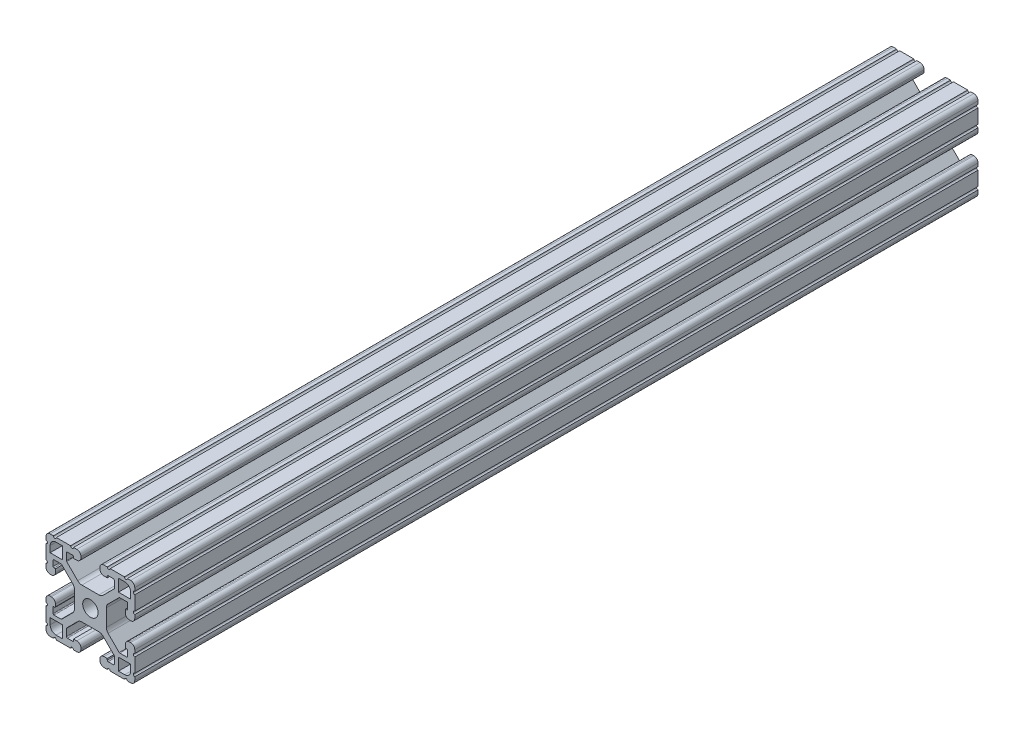
SolidWorks part; units mm, degrees
ref_plane "Front Plane" through (0, 0, 0) normal (0, 0, 1) x (1, 0, 0)
ref_plane "Top Plane" through (0, 0, 0) normal (0, 1, 0) x (1, 0, 0)
ref_plane "Right Plane" through (0, 0, 0) normal (1, 0, 0) x (0, 0, -1)
sketch "Sketch1" plane through (0, 0, 0) normal (0, 0, 1) x (1, 0, 0)
  line L0 (0, -19.05) -> (0, 19.05) construction
  line L1 (19.05, 0) -> (-19.05, 0) construction
  line L2 (4.064, 19.05) -> (-4.064, 19.05) construction
  line L3 (0, -6.858) -> (0, 6.858) construction
  line L4 (-4.064, 19.05) -> (-4.064, 14.986) construction
  line L5 (19.05, -10.287) -> (19.05, 10.287) construction
  line L6 (0, -3.302) -> (0, 3.302) construction
  point P4 (0, 0)
  point P8 (0, 0)
  point P11 (0, 19.05)
  point P14 (0, 0)
  point P18 (19.05, 0)
  point P21 (0, 0)
  dimension "Rail Width" = 38.1
  dimension "Rail Height" = 38.1
  dimension "T-Slot Width" = 8.128
  dimension "Thickness" = 4.064
  dimension "Opening Width" = 20.574
  dimension "Center Hole Diameter" = 6.604
  dimension "Slot Depth" = 12.192
sketch "Sketch2" plane through (0, 0, 0) normal (1, 0, 0) x (0, 0, -1)
  line L0 (-180.975, 0) -> (180.975, 0) construction
  line L1 (0, 19.05) -> (0, -19.05) construction
  line L2 (-25.4, 19.05) -> (25.4, 19.05) construction
  line L4 (3048, -19.05) -> (-3048, -19.05) construction
  point P0 (130.175, 0)
  point P3 (-130.175, 0)
  point P4 (0, 0)
  dimension "D1" = 50.8
  dimension "Rep Length" = 361.95
  dimension "D2" = 50.8
  dimension "Length Range [Min]" = 50.8
  dimension "Length Range [Max]" = 6096
sketch "Sketch3" plane through (0, 0, 0) normal (0, 0, 1) x (1, 0, 0)
  line L1 (19.05, -19.05) -> (-19.05, -19.05)
  line L2 (19.05, -19.05) -> (19.05, 19.05)
  line L3 (19.05, 19.05) -> (-19.05, 19.05)
  line L4 (-19.05, -19.05) -> (-19.05, 19.05)
  line L5 (19.05, -19.05) -> (-19.05, 19.05) construction
  line L6 (19.05, 19.05) -> (-19.05, -19.05) construction
  point P0 (0, 0)
extrude "Boss-Extrude1" add sketch "Sketch3" along normal up to vertex (180.975 mm away) and the other way up to vertex (180.975 mm away) up to point (0, 0, 180.975) other way up to point (0, 0, -180.975)
sketch "Sketch4" plane through (0, 0, 180.975) normal (0, 0, 1) x (1, 0, 0)
  line L4 (4.064, 14.986) -> (4.064, 19.05)
  line L5 (7.239, 14.986) -> (4.064, 14.986)
  line L6 (19.05, 0) -> (-19.05, 0) construction
  line L7 (4.7027, 6.858) -> (-4.7027, 6.858)
  line L8 (-4.7027, 6.858) -> (-10.287, 12.4423)
  line L37 (-19.05, 19.05) -> (-19.05, -19.05) construction
  line L38 (-19.05, -19.05) -> (19.05, -19.05) construction
  line L39 (-10.287, 12.4423) -> (-10.287, 16.002)
  line L40 (-10.287, 16.002) -> (-7.239, 16.002)
  line L41 (-7.239, 16.002) -> (-7.239, 14.986)
  line L42 (-7.239, 14.986) -> (-4.064, 14.986)
  line L43 (-4.064, 14.986) -> (-4.064, 19.05)
  line L44 (-4.064, 19.05) -> (4.064, 19.05)
  line L45 (0, 19.05) -> (0, 0) construction
  line L46 (-19.05, 19.05) -> (0, 0) construction
  line L47 (7.239, 16.002) -> (7.239, 14.986)
  line L48 (10.287, 16.002) -> (7.239, 16.002)
  line L49 (10.287, 12.4423) -> (10.287, 16.002)
  line L50 (4.7027, 6.858) -> (10.287, 12.4423)
  line L51 (-19.05, 0) -> (19.05, 0) construction
  line L52 (4.7027, -6.858) -> (10.287, -12.4423)
  line L53 (10.287, -12.4423) -> (10.287, -16.002)
  line L54 (10.287, -16.002) -> (7.239, -16.002)
  line L55 (7.239, -16.002) -> (7.239, -14.986)
  line L56 (-4.064, -19.05) -> (4.064, -19.05)
  line L57 (-4.064, -14.986) -> (-4.064, -19.05)
  line L58 (-7.239, -14.986) -> (-4.064, -14.986)
  line L59 (-7.239, -16.002) -> (-7.239, -14.986)
  line L60 (-10.287, -16.002) -> (-7.239, -16.002)
  line L61 (-10.287, -12.4423) -> (-10.287, -16.002)
  line L62 (-4.7027, -6.858) -> (-10.287, -12.4423)
  line L63 (4.7027, -6.858) -> (-4.7027, -6.858)
  line L64 (7.239, -14.986) -> (4.064, -14.986)
  line L65 (4.064, -14.986) -> (4.064, -19.05)
  line L66 (-6.858, -4.7027) -> (-12.4423, -10.287)
  line L67 (-12.4423, -10.287) -> (-16.002, -10.287)
  line L68 (-16.002, -10.287) -> (-16.002, -7.239)
  line L69 (-16.002, -7.239) -> (-14.986, -7.239)
  line L70 (-19.05, 4.064) -> (-19.05, -4.064)
  line L71 (-14.986, 4.064) -> (-19.05, 4.064)
  line L72 (-14.986, 7.239) -> (-14.986, 4.064)
  line L73 (-16.002, 7.239) -> (-14.986, 7.239)
  line L74 (-16.002, 10.287) -> (-16.002, 7.239)
  line L75 (-12.4423, 10.287) -> (-16.002, 10.287)
  line L76 (-6.858, 4.7027) -> (-12.4423, 10.287)
  line L77 (-6.858, -4.7027) -> (-6.858, 4.7027)
  line L78 (-14.986, -7.239) -> (-14.986, -4.064)
  line L79 (-14.986, -4.064) -> (-19.05, -4.064)
  line L80 (14.986, -4.064) -> (19.05, -4.064)
  line L81 (14.986, -7.239) -> (14.986, -4.064)
  line L82 (6.858, -4.7027) -> (6.858, 4.7027)
  line L83 (6.858, 4.7027) -> (12.4423, 10.287)
  line L84 (12.4423, 10.287) -> (16.002, 10.287)
  line L85 (16.002, 10.287) -> (16.002, 7.239)
  line L86 (16.002, 7.239) -> (14.986, 7.239)
  line L87 (14.986, 7.239) -> (14.986, 4.064)
  line L88 (14.986, 4.064) -> (19.05, 4.064)
  line L89 (19.05, 4.064) -> (19.05, -4.064)
  line L90 (16.002, -7.239) -> (14.986, -7.239)
  line L91 (16.002, -10.287) -> (16.002, -7.239)
  line L92 (12.4423, -10.287) -> (16.002, -10.287)
  line L93 (6.858, -4.7027) -> (12.4423, -10.287)
  line L94 (19.05, -19.05) -> (19.05, 19.05) construction
  line L95 (12.065, 17.272) -> (17.272, 17.272)
  line L96 (12.065, 17.272) -> (12.065, 12.065)
  line L97 (12.065, 12.065) -> (17.272, 12.065)
  line L98 (17.272, 17.272) -> (17.272, 12.065)
  line L99 (19.05, 19.05) -> (-19.05, 19.05) construction
  line L100 (17.272, -17.272) -> (17.272, -12.065)
  line L101 (12.065, -17.272) -> (17.272, -17.272)
  line L102 (12.065, -17.272) -> (12.065, -12.065)
  line L103 (12.065, -12.065) -> (17.272, -12.065)
  line L104 (-17.272, 17.272) -> (-17.272, 12.065)
  line L105 (-12.065, 12.065) -> (-17.272, 12.065)
  line L106 (-12.065, 17.272) -> (-12.065, 12.065)
  line L107 (-12.065, 17.272) -> (-17.272, 17.272)
  line L108 (-12.065, -12.065) -> (-17.272, -12.065)
  line L109 (-12.065, -17.272) -> (-12.065, -12.065)
  line L110 (-12.065, -17.272) -> (-17.272, -17.272)
  line L111 (-17.272, -17.272) -> (-17.272, -12.065)
  circle A5 centre (0, 0) radius 3.302
  point P21 (0, 6.858)
  point P23 (0, -6.858)
  point P38 (-6.858, 0)
  point P53 (6.858, 0)
  dimension "D1" = 20.574
  dimension "D2" = 3.048
  dimension "D3" = 3.048
  dimension "D4" = 3.048
  dimension "D5" = 1.778
  dimension "D6" = 1.778
  dimension "D7" = 1.778
extrude "Cut-Extrude1" cut sketch "Sketch4" against normal through all
sketch "Sketch5" plane through (0, 0, 180.975) normal (0, 0, 1) x (1, 0, 0)
  line L4 (-4.064, 19.05) -> (-19.05, 19.05) construction
  line L26 (-19.05, 19.05) -> (-19.05, 4.064) construction
  line L27 (-15.875, 19.05) -> (-14.605, 19.05)
  line L28 (-8.509, 19.05) -> (-7.239, 19.05)
  line L29 (-19.05, 15.875) -> (-19.05, 14.605)
  line L30 (-19.05, 8.509) -> (-19.05, 7.239)
  line L31 (8.509, 19.05) -> (7.239, 19.05)
  line L32 (15.875, 19.05) -> (14.605, 19.05)
  line L33 (19.05, 15.875) -> (19.05, 14.605)
  line L34 (19.05, 8.509) -> (19.05, 7.239)
  line L35 (19.05, -8.509) -> (19.05, -7.239)
  line L36 (19.05, -15.875) -> (19.05, -14.605)
  line L37 (15.875, -19.05) -> (14.605, -19.05)
  line L38 (8.509, -19.05) -> (7.239, -19.05)
  line L39 (-8.509, -19.05) -> (-7.239, -19.05)
  line L40 (-15.875, -19.05) -> (-14.605, -19.05)
  line L41 (-19.05, -15.875) -> (-19.05, -14.605)
  line L42 (-19.05, -8.509) -> (-19.05, -7.239)
  line L43 (19.05, 19.05) -> (4.064, 19.05) construction
  line L44 (19.05, 4.064) -> (19.05, 19.05) construction
  line L48 (-14.986, 4.064) -> (-19.05, 4.064) construction
  line L49 (-4.064, 14.986) -> (-4.064, 19.05) construction
  arc A8 (-15.875, 19.05) -> (-14.605, 19.05) centre (-15.24, 19.05) ccw
  arc A9 (-8.509, 19.05) -> (-7.239, 19.05) centre (-7.874, 19.05) ccw
  arc A10 (-19.05, 14.605) -> (-19.05, 15.875) centre (-19.05, 15.24) ccw
  arc A11 (-19.05, 7.239) -> (-19.05, 8.509) centre (-19.05, 7.874) ccw
  arc A12 (7.239, 19.05) -> (8.509, 19.05) centre (7.874, 19.05) ccw
  arc A13 (14.605, 19.05) -> (15.875, 19.05) centre (15.24, 19.05) ccw
  arc A14 (19.05, 15.875) -> (19.05, 14.605) centre (19.05, 15.24) ccw
  arc A15 (19.05, 8.509) -> (19.05, 7.239) centre (19.05, 7.874) ccw
  arc A16 (19.05, -7.239) -> (19.05, -8.509) centre (19.05, -7.874) ccw
  arc A17 (19.05, -14.605) -> (19.05, -15.875) centre (19.05, -15.24) ccw
  arc A18 (15.875, -19.05) -> (14.605, -19.05) centre (15.24, -19.05) ccw
  arc A19 (8.509, -19.05) -> (7.239, -19.05) centre (7.874, -19.05) ccw
  arc A20 (-7.239, -19.05) -> (-8.509, -19.05) centre (-7.874, -19.05) ccw
  arc A21 (-14.605, -19.05) -> (-15.875, -19.05) centre (-15.24, -19.05) ccw
  arc A22 (-19.05, -15.875) -> (-19.05, -14.605) centre (-19.05, -15.24) ccw
  arc A23 (-19.05, -8.509) -> (-19.05, -7.239) centre (-19.05, -7.874) ccw
  dimension "D2" = 0.635
  dimension "D4" = 3.81
  dimension "D5" = 3.81
  dimension "D1" = 3.81
  dimension "D3" = 3.81
  dimension "D7" = 4
extrude "Cut-Extrude2" cut sketch "Sketch5" against normal through all
fillet "Fillet1" radius 2.54 12 edges at (-6.858, 4.7027, 0) (-6.858, -4.7027, 0) (4.7027, -6.858, 0) (-4.7027, -6.858, 0) (6.858, -4.7027, 0) (6.858, 4.7027, 0) (4.7027, 6.858, 0) (-4.7027, 6.858, 0) (-17.272, 17.272, 0) (17.272, 17.272, 0) (17.272, -17.272, 0) (-17.272, -17.272, 0)
fillet "Fillet2" radius 1.778 20 edges at (19.05, -19.05, 0) (19.05, 19.05, 0) (-19.05, -19.05, 0) (-19.05, 19.05, 0) (-14.986, 4.064, 0) (-19.05, 4.064, 0) (-19.05, -4.064, 0) (-14.986, -4.064, 0) (-4.064, -19.05, 0) (-4.064, -14.986, 0) (4.064, -14.986, 0) (4.064, -19.05, 0) (19.05, -4.064, 0) (14.986, -4.064, 0) (19.05, 4.064, 0) (14.986, 4.064, 0) (4.064, 14.986, 0) (4.064, 19.05, 0) (-4.064, 19.05, 0) (-4.064, 14.986, 0)
fillet "Fillet3" radius 0.3969 24 edges at (-14.986, -7.239, 0) (-16.002, -10.287, 0) (-12.4423, -10.287, 0) (-12.4423, 10.287, 0) (-16.002, 7.239, 0) (-16.002, 10.287, 0) (-10.287, 12.4423, 0) (-7.239, 16.002, 0) (-10.287, 16.002, 0) (10.287, 16.002, 0) (7.239, 16.002, 0) (10.287, 12.4423, 0) (16.002, 10.287, 0) (12.4423, 10.287, 0) (16.002, 7.239, 0) (16.002, -7.239, 0) (16.002, -10.287, 0) (12.4423, -10.287, 0) (10.287, -12.4423, 0) (10.287, -16.002, 0) (7.239, -16.002, 0) (-7.239, -16.002, 0) (-10.287, -12.4423, 0) (-10.287, -16.002, 0)
equation "\"D4@Sketch5\"=\"D3@Sketch5\""
equation "\"D5@Sketch5\"=\"D4@Sketch5\""
equation "\"D1@Sketch4\"=\"Opening Width@Sketch1\""
